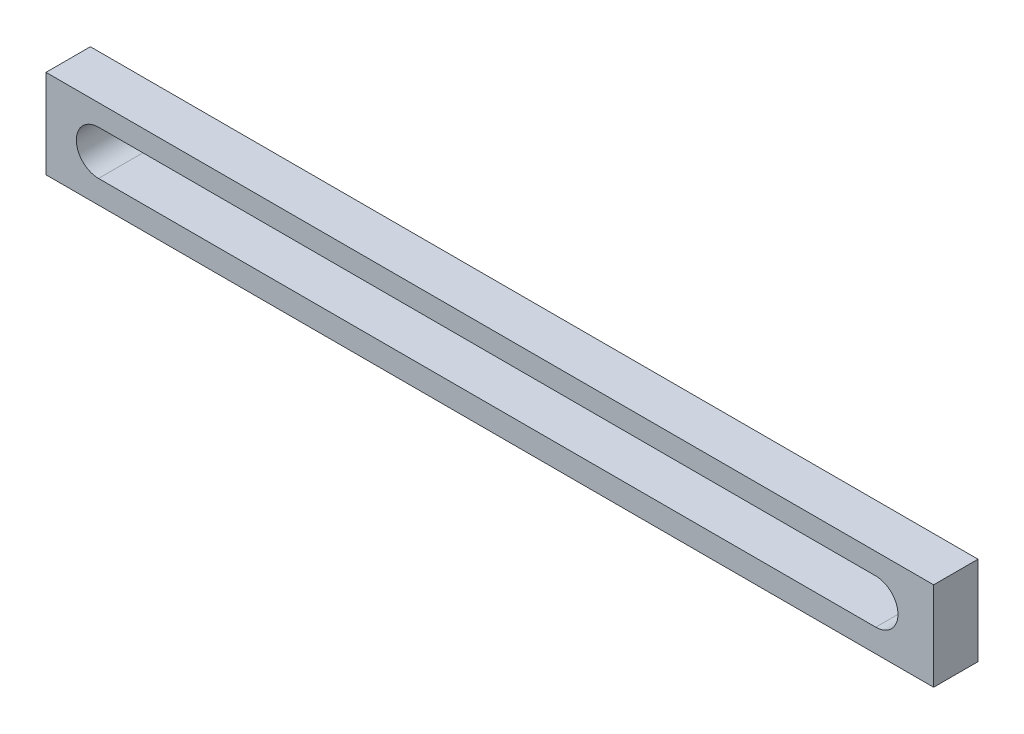
SolidWorks part; units mm, degrees
ref_plane "前视基准面" through (0, 0, 0) normal (0, 0, 1) x (1, 0, 0)
ref_plane "上视基准面" through (0, 0, 0) normal (0, 1, 0) x (1, 0, 0)
ref_plane "右视基准面" through (0, 0, 0) normal (1, 0, 0) x (0, 0, -1)
sketch "草图1" plane through (0, 0, 0) normal (0, 0, 1) x (1, 0, 0)
  line L0 (5.9164, -2.3937) -> (93.482, -2.3937)
  line L1 (0, 0) -> (100, 0)
  line L2 (0, 0) -> (0, -10)
  line L3 (0, -10) -> (100, -10)
  line L4 (100, 0) -> (100, -10)
  line L5 (5.9164, -7.3937) -> (93.482, -7.3937)
  arc A0 (5.9164, -2.3937) -> (5.9164, -7.3937) centre (5.9164, -4.8937) ccw
  arc A1 (93.482, -7.3937) -> (93.482, -2.3937) centre (93.482, -4.8937) ccw
  dimension "D1" = 100
  dimension "D2" = 10
extrude "凸台-拉伸1" add sketch "草图1" along normal blind 5
